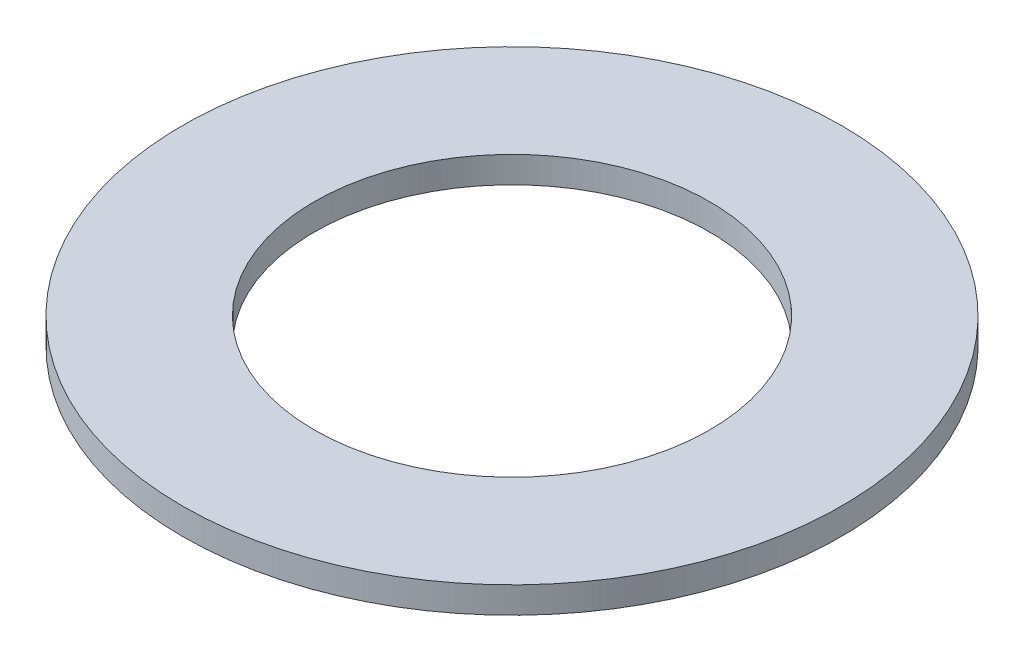
SolidWorks part; units mm, degrees
material "AISI 304"
ref_plane "前视基准面" through (0, 0, 0) normal (0, 0, 1) x (1, 0, 0)
ref_plane "上视基准面" through (0, 0, 0) normal (0, 1, 0) x (1, 0, 0)
ref_plane "右视基准面" through (0, 0, 0) normal (1, 0, 0) x (0, 0, -1)
other "Configuration Table"
sketch "草图3" plane through (0, 0, 0) normal (0, 1, 0) x (1, 0, 0)
  circle A0 centre (0, 0) radius 1.5
  circle A1 centre (0, 0) radius 2.5
  dimension "D1" = 3
  dimension "D2" = 5
extrude "凸台-拉伸1" add sketch "草图3" along normal mid plane 0.2
